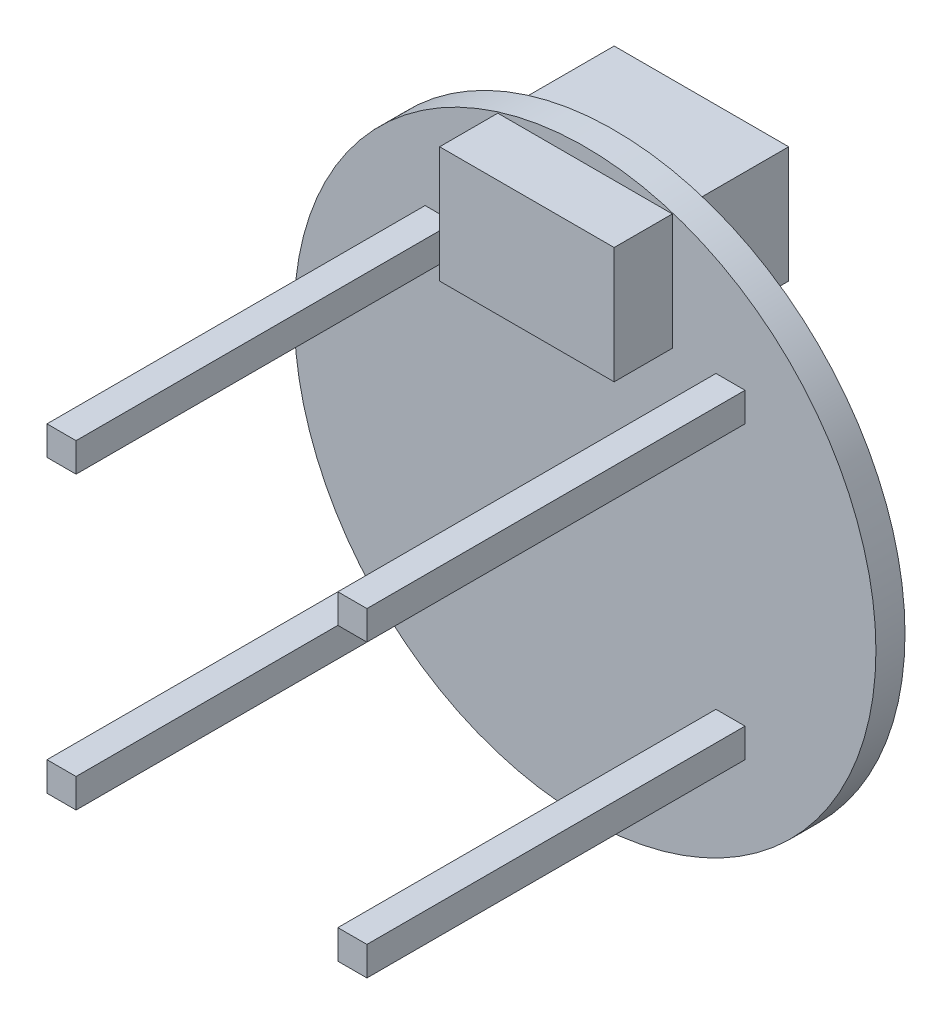
SolidWorks part; units mm, degrees
ref_plane "前视基准面" through (0, 0, 0) normal (0, 0, 1) x (1, 0, 0)
ref_plane "上视基准面" through (0, 0, 0) normal (0, 1, 0) x (1, 0, 0)
ref_plane "右视基准面" through (0, 0, 0) normal (1, 0, 0) x (0, 0, -1)
other "Configuration Table"
sketch "草图1" plane through (0, 0, 0) normal (0, 0, 1) x (1, 0, 0)
  circle A0 centre (0, 0) radius 500
extrude "凸台-拉伸1" add sketch "草图1" along normal blind 50
sketch "草图2" plane through (0, 0, 0) normal (0, 0, 1) x (1, 0, 0)
  line L1 (225, 225) -> (275, 225)
  line L2 (225, 225) -> (225, 275)
  line L3 (225, 275) -> (275, 275)
  line L4 (275, 225) -> (275, 275)
  line L5 (225, 225) -> (275, 275) construction
  line L6 (225, 275) -> (275, 225) construction
  point P0 (250, 250)
extrude "凸台-拉伸2" add sketch "草图2" along normal blind 700
sketch "草图3" plane through (0, 0, 0) normal (0, 0, 1) x (1, 0, 0)
  line L1 (-275, 225) -> (-225, 225)
  line L2 (-275, 225) -> (-275, 275)
  line L3 (-275, 275) -> (-225, 275)
  line L4 (-225, 225) -> (-225, 275)
  line L5 (-275, 225) -> (-225, 275) construction
  line L6 (-275, 275) -> (-225, 225) construction
  point P0 (-250, 250)
extrude "凸台-拉伸3" add sketch "草图3" along normal blind 700
sketch "草图4" plane through (0, 0, 0) normal (0, 0, 1) x (1, 0, 0)
  line L1 (225, -275) -> (275, -275)
  line L2 (225, -275) -> (225, -225)
  line L3 (225, -225) -> (275, -225)
  line L4 (275, -275) -> (275, -225)
  line L5 (225, -275) -> (275, -225) construction
  line L6 (225, -225) -> (275, -275) construction
  point P0 (250, -250)
extrude "凸台-拉伸4" add sketch "草图4" along normal blind 700
sketch "草图5" plane through (0, 0, 0) normal (0, 0, 1) x (1, 0, 0)
  line L1 (-275, -275) -> (-225, -275)
  line L2 (-275, -275) -> (-275, -225)
  line L3 (-275, -225) -> (-225, -225)
  line L4 (-225, -275) -> (-225, -225)
  line L5 (-275, -275) -> (-225, -225) construction
  line L6 (-275, -225) -> (-225, -275) construction
  point P0 (-250, -250)
extrude "凸台-拉伸5" add sketch "草图5" along normal blind 700
sketch "草图6" plane through (0, 275, 0) normal (0, 1, 0) x (1, 0, 0)
  line L1 (-150, -150) -> (150, -150)
  line L2 (-150, -150) -> (-150, 150)
  line L3 (-150, 150) -> (150, 150)
  line L4 (150, -150) -> (150, 150)
  line L5 (-150, -150) -> (150, 150) construction
  line L6 (-150, 150) -> (150, -150) construction
  point P0 (0, 0)
extrude "凸台-拉伸6" add sketch "草图6" along normal blind 200
